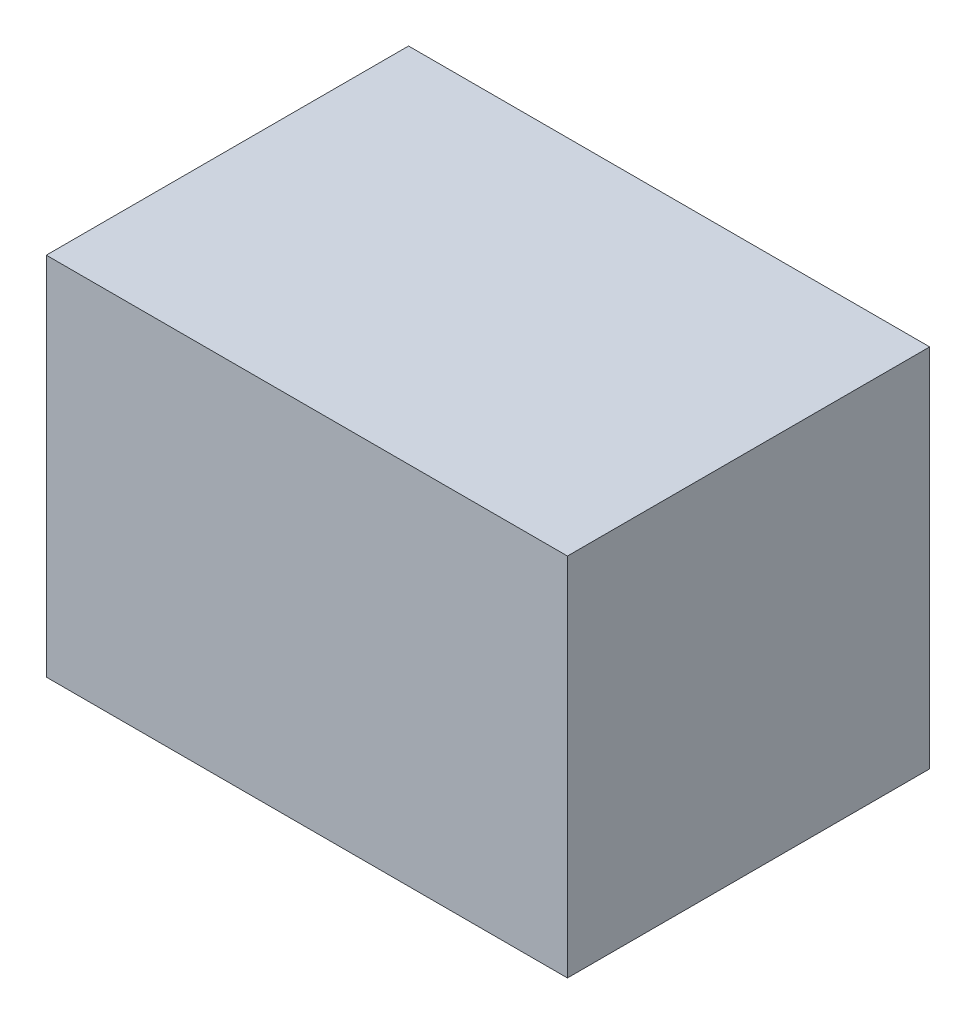
SolidWorks part; units mm, degrees
ref_plane "Alzado" through (0, 0, 0) normal (0, 0, 1) x (1, 0, 0)
ref_plane "Planta" through (0, 0, 0) normal (0, 1, 0) x (1, 0, 0)
ref_plane "Vista lateral" through (0, 0, 0) normal (1, 0, 0) x (0, 0, -1)
sketch "Croquis1" plane through (0, 0, 0) normal (0, 1, 0) x (1, 0, 0)
  line L1 (-8.2, 5.7) -> (8.2, 5.7)
  line L2 (-8.2, 5.7) -> (-8.2, -5.7)
  line L3 (-8.2, -5.7) -> (8.2, -5.7)
  line L4 (8.2, 5.7) -> (8.2, -5.7)
  line L5 (-8.2, 5.7) -> (8.2, -5.7) construction
  line L6 (-8.2, -5.7) -> (8.2, 5.7) construction
  point P0 (0, 0)
  dimension "D1" = 16.4
  dimension "D2" = 11.4
extrude "Saliente-Extruir2" add sketch "Croquis1" along normal blind 11.5
